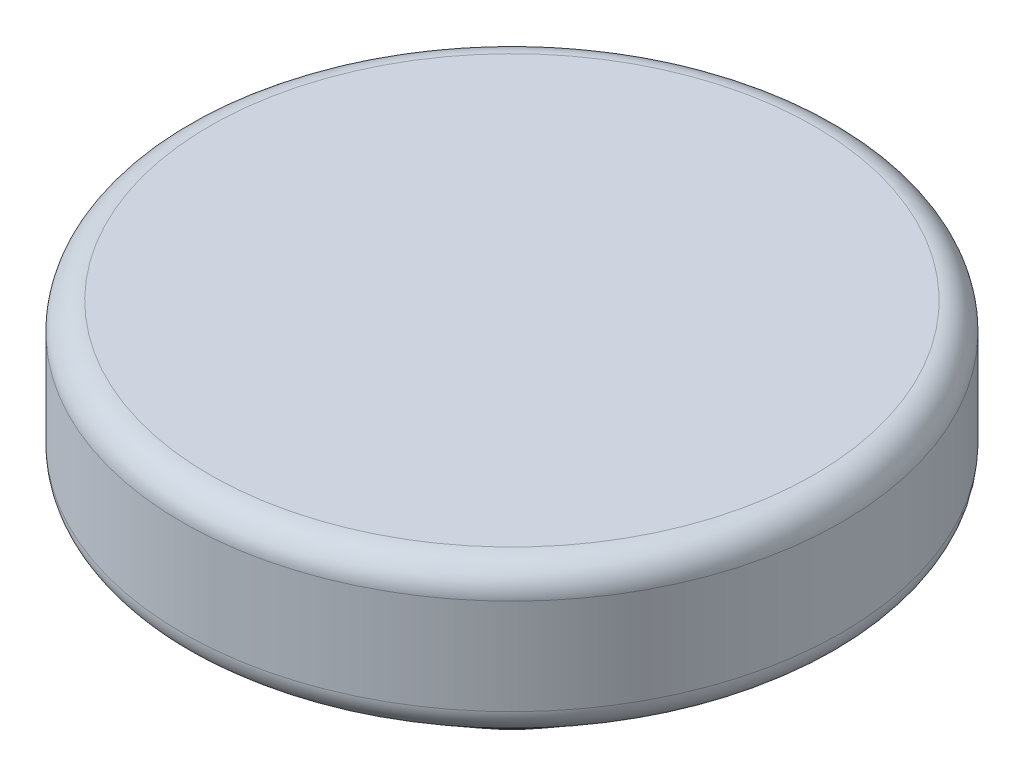
SolidWorks part; units mm, degrees
ref_plane "Front Plane" through (0, 0, 0) normal (0, 0, 1) x (1, 0, 0)
ref_plane "Top Plane" through (0, 0, 0) normal (0, 1, 0) x (1, 0, 0)
ref_plane "Right Plane" through (0, 0, 0) normal (1, 0, 0) x (0, 0, -1)
sketch "Sketch1" plane through (0, 0, 0) normal (0, 0, 1) x (1, 0, 0)
  line L9 (0, -44.991) -> (25, -44.991)
  line L10 (25, -44.991) -> (60, -19.991)
  line L11 (60, -19.991) -> (60, 5.009)
  line L13 (60, 5.009) -> (0, 5.009)
  line L17 (0, 5.009) -> (0, -44.991)
  dimension "D1" = 25
  dimension "D2" = 60
  dimension "D3" = 50
  dimension "D4" = 25
revolve "Revolve3" add sketch "Sketch1" angle 360 about L17
fillet "Fillet2" radius 5 1 edges at (-60, 5.009, 0)
fillet "Fillet3" radius 5 1 edges at (-60, -19.991, 0)
fillet "Fillet4" radius 6 1 edges at (-25, -44.991, 0)
